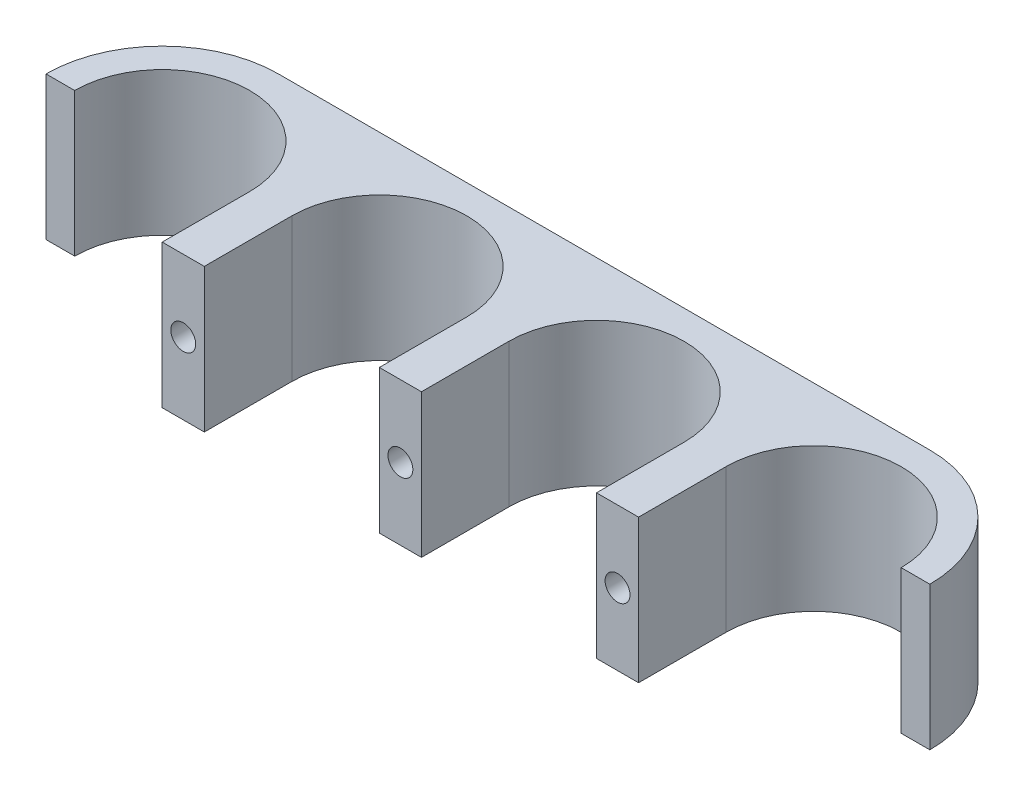
SolidWorks part; units mm, degrees
ref_plane "Front Plane" through (0, 0, 0) normal (0, 0, 1) x (1, 0, 0)
ref_plane "Top Plane" through (0, 0, 0) normal (0, 1, 0) x (1, 0, 0)
ref_plane "Right Plane" through (0, 0, 0) normal (1, 0, 0) x (0, 0, -1)
sketch "Sketch1" plane through (0, 0, 0) normal (0, 1, 0) x (1, 0, 0)
  line L0 (2.2, 0) -> (2.2, -9.15)
  line L2 (0, -14.1062) -> (0, 53.0997) construction
  line L22 (2.2, -9.15) -> (-2.2, -9.15)
  line L23 (20.5, 0) -> (20.5, -9.15)
  line L24 (20.5, -9.15) -> (24.9, -9.15)
  line L25 (24.9, -9.15) -> (24.9, 0)
  line L26 (43.2, 0) -> (46.2, 0)
  line L27 (34.05, 12.15) -> (-34.05, 12.15)
  line L28 (-43.2, 0) -> (-46.2, 0)
  line L29 (-24.9, -9.15) -> (-24.9, 0)
  line L30 (-20.5, -9.15) -> (-24.9, -9.15)
  line L31 (-20.5, 0) -> (-20.5, -9.15)
  line L32 (-2.2, 0) -> (-2.2, -9.15)
  circle A4 centre (11.35, 0) radius 9.15 construction
  arc A5 (2.2, 0) -> (20.5, 0) centre (11.35, 0) cw
  circle A6 centre (34.05, 0) radius 9.15 construction
  arc A8 (46.2, 0) -> (34.05, 12.15) centre (34.05, 0) ccw
  arc A10 (24.9, 0) -> (43.2, 0) centre (34.05, 0) cw
  circle A11 centre (-34.05, 0) radius 9.15 construction
  circle A12 centre (-11.35, 0) radius 9.15 construction
  arc A13 (-24.9, 0) -> (-43.2, 0) centre (-34.05, 0) ccw
  arc A14 (-46.2, 0) -> (-34.05, 12.15) centre (-34.05, 0) cw
  arc A15 (-2.2, 0) -> (-20.5, 0) centre (-11.35, 0) ccw
  point P28 (0, 24.7)
  point P29 (0, 15.55)
  point P30 (0, 12.15)
  point P33 (0, -9.15)
  dimension "D1" = 2.2
  dimension "D3" = 9.15
  dimension "D2" = 4.4
  dimension "D4" = 3
extrude "Boss-Extrude1" add sketch "Sketch1" along normal blind 15
hole_wizard "M2 Clearance Hole2" positions "Sketch4" profile "Sketch5" hole size "M2" standard "ANSI Metric" end condition through all
sketch "Sketch4" plane through (0, 0, -12.15) normal (0, 0, -1) x (-1, 0, 0)
  line L0 (-34.05, 0) -> (34.05, 0) construction
  point P0 (0, 7.5)
  point P2 (-22.7, 7.5)
  point P4 (22.7, 7.5)
  point P9 (0, 0)
  dimension "D1" = 7.5
  dimension "D2" = 7.5
  dimension "D3" = 7.5
  dimension "D4" = 0
  dimension "D5" = 22.7
  dimension "D6" = 22.7
sketch "Sketch5" plane through (0, 7.5, -12.15) normal (1, 0, 0) x (0, 1, 0)
  line L0 (0, 0) -> (0, 21.3)
  line L1 (0, 21.3) -> (1.3, 21.3)
  line L2 (1.3, 21.3) -> (1.3, 0)
  line L5 (1.3, 0) -> (0, 0)
  line L11 (0, -6.35) -> (0, 107.95) construction
  dimension "Thru Hole Dia." = 2.6
  dimension "Thru Hole Depth" = 21.3
